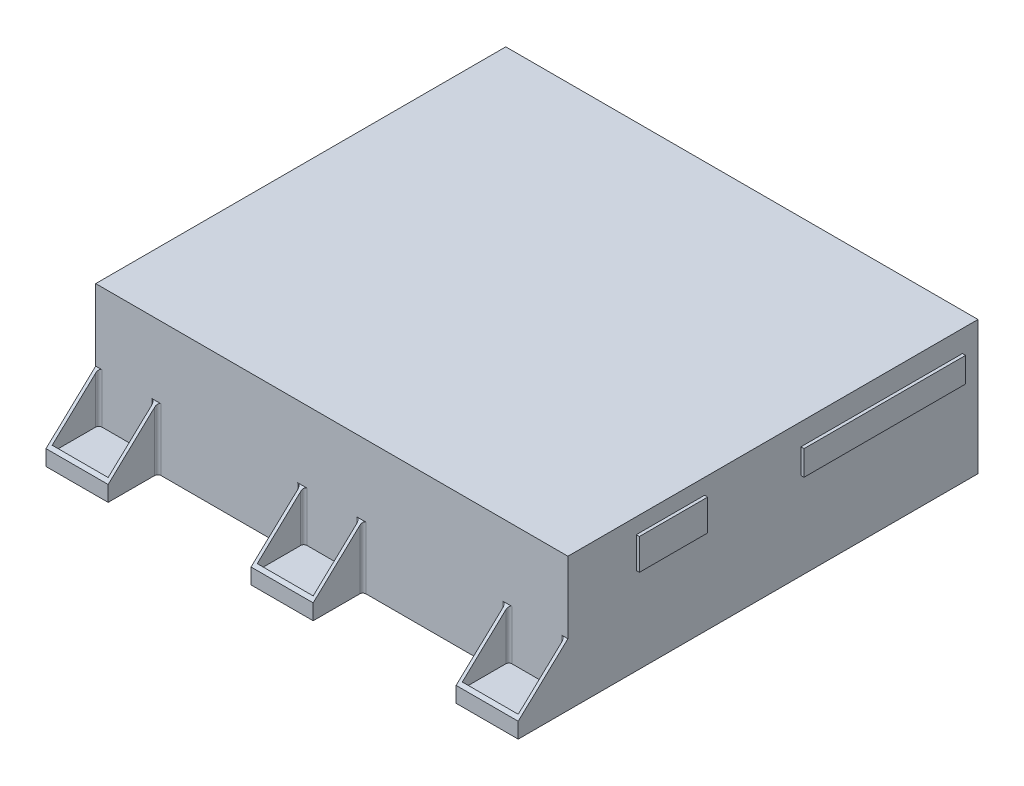
SolidWorks part; units mm, degrees
ref_plane "Front Plane" through (0, 0, 0) normal (0, 0, 1) x (1, 0, 0)
ref_plane "Top Plane" through (0, 0, 0) normal (0, 1, 0) x (1, 0, 0)
ref_plane "Right Plane" through (0, 0, 0) normal (1, 0, 0) x (0, 0, -1)
sketch "Sketch1" plane through (0, 0, 0) normal (0, 0, 1) x (1, 0, 0)
  line L1 (76, -20) -> (-76, -20)
  line L2 (76, -20) -> (76, 20)
  line L3 (76, 20) -> (-76, 20)
  line L4 (-76, -20) -> (-76, 20)
  line L5 (76, -20) -> (-76, 20) construction
  line L6 (76, 20) -> (-76, -20) construction
  point P0 (0, 0)
  dimension "D1" = 40
  dimension "D2" = 152
extrude "Boss-Extrude1" add sketch "Sketch1" along normal blind 132
sketch "Sketch2" plane through (0, 20, 0) normal (0, 1, 0) x (1, 0, 0)
  line L1 (-76, 0) -> (76, 0)
  line L2 (-76, 0) -> (-76, -132)
  line L3 (-76, -132) -> (76, -132)
  line L4 (76, 0) -> (76, -132)
extrude "Boss-Extrude2" add sketch "Sketch2" along normal blind 3
sketch "Sketch4" plane through (0, 0, 132) normal (0, 0, 1) x (1, 0, 0)
  line L0 (-76, 0) -> (76, 0) construction
  line L1 (-76, 23) -> (-76, -20) construction
  line L2 (76, -20) -> (76, 23) construction
  line L3 (-76, -20) -> (76, -20) construction
  line L4 (-76, 0) -> (-56, 0)
  line L5 (-76, 0) -> (-76, -20)
  line L6 (-76, -20) -> (-56, -20)
  line L7 (-56, 0) -> (-56, -20)
  line L9 (76, 0) -> (56, 0)
  line L10 (76, 0) -> (76, -20)
  line L11 (76, -20) -> (56, -20)
  line L12 (56, 0) -> (56, -20)
  line L13 (-10, 0) -> (10, 0)
  line L14 (-10, 0) -> (-10, -20)
  line L15 (-10, -20) -> (10, -20)
  line L16 (10, 0) -> (10, -20)
  dimension "D1" = 20
  dimension "D2" = 20
  dimension "D3" = 20
  dimension "D4" = 66
extrude "Boss-Extrude3" add sketch "Sketch4" along normal blind 16
sketch "Sketch7" plane through (0, 0, 0) normal (0, 1, 0) x (1, 0, 0)
  line L0 (-76, -132) -> (76, -132) construction
  line L1 (57, -132) -> (75, -132)
  line L2 (57, -132) -> (57, -147)
  line L3 (57, -147) -> (75, -147)
  line L4 (75, -132) -> (75, -147)
  line L5 (-76, -148) -> (-76, -132) construction
  line L6 (-9, -132) -> (9, -132)
  line L7 (-9, -132) -> (-9, -147)
  line L8 (-9, -147) -> (9, -147)
  line L9 (9, -132) -> (9, -147)
  line L10 (-75, -132) -> (-57, -132)
  line L11 (-75, -132) -> (-75, -147)
  line L12 (-75, -147) -> (-57, -147)
  line L13 (-57, -132) -> (-57, -147)
  line L14 (-10, -148) -> (-10, -132) construction
  line L15 (56, -148) -> (56, -132) construction
  dimension "D1" = 15
  dimension "D2" = 18
  dimension "D3" = 1
  dimension "D4" = 18
  dimension "D5" = 1
  dimension "D6" = 15
  dimension "D7" = 15
  dimension "D8" = 18
  dimension "D9" = 1
extrude "Cut-Extrude1" cut sketch "Sketch7" against normal blind 16
sketch "Sketch8" plane through (76, 0, 0) normal (1, 0, 0) x (0, 0, -1)
  line L0 (-132, 0) -> (-148, -15)
  line L1 (-132, 0) -> (-148, 0) construction
  line L2 (-132, 0) -> (-132, -20) construction
  line L3 (-132, -20) -> (-148, -20) construction
  line L4 (-148, 0) -> (-148, -20) construction
  line L5 (-148, -15) -> (-148, 0)
  line L6 (-148, 0) -> (-132, 0)
  dimension "D1" = 5
extrude "Cut-Extrude2" cut sketch "Sketch8" against normal through all
fillet "Fillet1" radius 1 10 edges at (10, -10, 132) (-9, -8, 132) (-56, -10, 132) (-75, -8, 132) (-57, -8, 132) (-10, -10, 132) (9, -8, 132) (56, -10, 132) (75, -8, 132) (57, -8, 132)
sketch "Sketch9" plane through (76, 0, 0) normal (1, 0, 0) x (0, 0, -1)
  line L0 (0, 8) -> (-132, 8) construction
  line L3 (0, -20) -> (0, 23) construction
  line L4 (-132, 0) -> (-132, 23) construction
  line L5 (-148, -20) -> (0, -20) construction
  line L7 (-110, 8) -> (-88, 8)
  line L8 (-110, 8) -> (-110, 18)
  line L9 (-110, 18) -> (-88, 18)
  line L10 (-88, 8) -> (-88, 18)
  line L11 (-57, 8) -> (-5, 8)
  line L12 (-57, 8) -> (-57, 16)
  line L13 (-57, 16) -> (-5, 16)
  line L14 (-5, 8) -> (-5, 16)
  dimension "D1" = 28
  dimension "D2" = 10
  dimension "D3" = 22
  dimension "D4" = 52
  dimension "D5" = 8
  dimension "D6" = 88
  dimension "D7" = 5
extrude "Boss-Extrude4" add sketch "Sketch9" along normal blind 1
